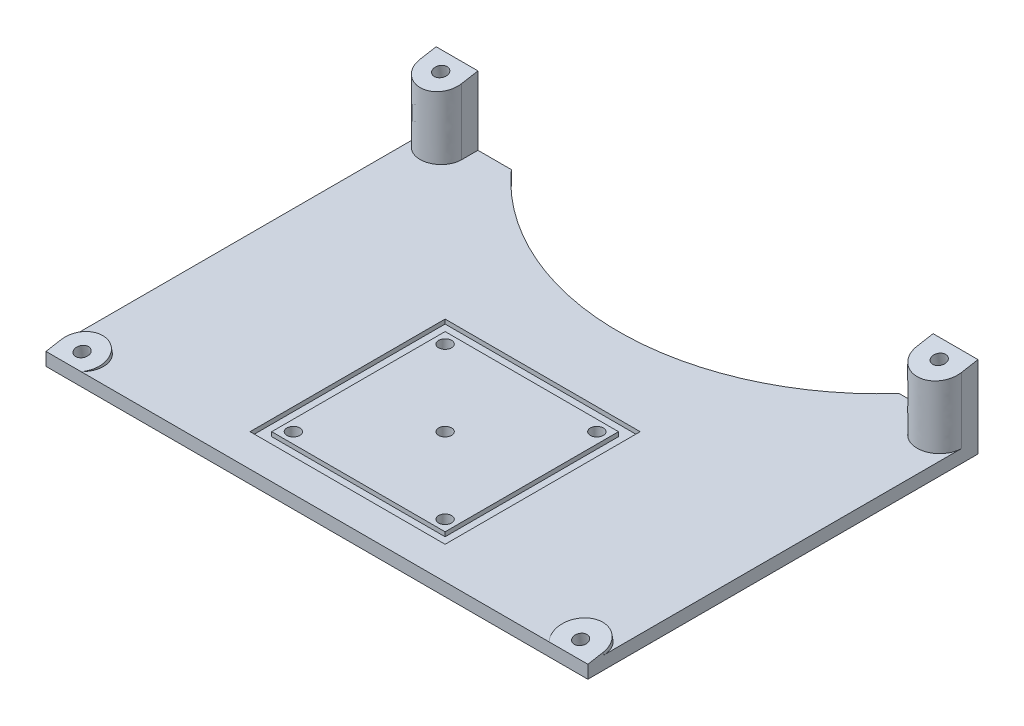
SolidWorks part; units mm, degrees
ref_plane "前视基准面" through (0, 0, 0) normal (0, 0, 1) x (1, 0, 0)
ref_plane "上视基准面" through (0, 0, 0) normal (0, 1, 0) x (1, 0, 0)
ref_plane "右视基准面" through (0, 0, 0) normal (1, 0, 0) x (0, 0, -1)
other "Configuration Table"
sketch "草图1" plane through (0, 0, 0) normal (0, 1, 0) x (1, 0, 0)
  line L1 (-62.5, 45) -> (62.5, 45)
  line L2 (-62.5, 45) -> (-62.5, -45)
  line L3 (-62.5, -45) -> (62.5, -45)
  line L4 (62.5, 45) -> (62.5, -45)
  line L5 (-62.5, 45) -> (62.5, -45) construction
  line L6 (-62.5, -45) -> (62.5, 45) construction
  point P0 (0, 0)
  dimension "D1" = 125
  dimension "D2" = 90
extrude "凸台-拉伸1" add sketch "草图1" along normal blind 3
sketch "草图3" plane through (62.5, 0, 0) normal (1, 0, 0) x (0, 0, -1)
  line L0 (-45, 3) -> (45, 18.8694)
  line L2 (45, 18.8694) -> (45, 3)
  line L3 (-45, 3) -> (45, 3) construction
  line L4 (-45, 3) -> (45, 3)
  dimension "D1" = 10
extrude "凸台-拉伸2" add sketch "草图3" against normal up to surface (125 mm away) up to face at (-62.5, 1.5, 0)
sketch "草图4" plane through (0, 10.605, 1.8699) normal (0, 0.9848, 0.1736) x (1, 0, 0)
  line L3 (-57.6776, 43.7689) -> (57.3224, 43.7689) construction
  line L4 (-57.6776, 43.7689) -> (-57.6776, -40.2311) construction
  line L5 (-57.6776, -40.2311) -> (57.3224, -40.2311) construction
  line L6 (57.3224, 43.7689) -> (57.3224, -40.2311) construction
  line L7 (-57.6776, 43.7689) -> (57.3224, -40.2311) construction
  line L8 (-57.6776, -40.2311) -> (57.3224, 43.7689) construction
  circle A0 centre (-57.6776, 43.7689) radius 1.5
  circle A1 centre (-57.6776, -40.2311) radius 1.5
  circle A2 centre (57.3224, -40.2311) radius 1.5
  circle A3 centre (57.3224, 43.7689) radius 1.5
  point P8 (-0.1776, 1.7689)
  dimension "D3" = 3
  dimension "D4" = 3
  dimension "D5" = 3
  dimension "D6" = 3
  dimension "D1" = 84
  dimension "D2" = 115
extrude "切除-拉伸1" cut sketch "草图4" against normal through all
sketch "草图6" plane through (0, 10.605, 1.8699) normal (0, 0.9848, 0.1736) x (1, 0, 0)
  line L0 (-62.5, 1.8988) -> (62.5, 1.8988) construction
  line L1 (-62.5, -43.7954) -> (-62.5, 47.593) construction
  line L2 (62.5, 47.593) -> (62.5, -43.7954) construction
  line L3 (0, 47.593) -> (0, -43.7954) construction
  line L4 (-62.5, 47.593) -> (62.5, 47.593) construction
  line L5 (-62.5, -43.7954) -> (62.5, -43.7954) construction
  line L6 (-62.5, 43.7689) -> (-62.5, -40.2311)
  line L7 (-54.7396, 47.593) -> (53.8318, 47.593)
  line L8 (62.5, 43.7689) -> (62.5, -40.2311)
  line L9 (-54.4294, -43.7954) -> (53.5669, -43.7954)
  arc A0 (-62.5, 43.7689) -> (-54.7396, 47.593) centre (-57.6776, 43.7689) ccw
  arc A1 (-54.4294, -43.7954) -> (-62.5, -40.2311) centre (-57.6776, -40.2311) ccw
  arc A2 (53.8318, 47.593) -> (62.5, 43.7689) centre (57.3224, 43.7689) ccw
  arc A3 (62.5, -40.2311) -> (53.5669, -43.7954) centre (57.3224, -40.2311) ccw
extrude "切除-拉伸2" cut sketch "草图6" against normal offset from surface (15.44 mm away) 3
sketch "草图7" plane through (0, 3, 0) normal (0, 1, 0) x (1, 0, 0)
  line L0 (-0.4313, -45) -> (-0.4313, -15) construction
  line L1 (-54.4294, -45) -> (53.5669, -45) construction
  line L3 (-17.9313, 2.5) -> (17.0687, 2.5) construction
  line L4 (-17.9313, 2.5) -> (-17.9313, -32.5) construction
  line L5 (-17.9313, -32.5) -> (17.0687, -32.5) construction
  line L6 (17.0687, 2.5) -> (17.0687, -32.5) construction
  line L7 (-17.9313, 2.5) -> (17.0687, -32.5) construction
  line L8 (-17.9313, -32.5) -> (17.0687, 2.5) construction
  circle A0 centre (-17.9313, 2.5) radius 1.5
  circle A1 centre (-17.9313, -32.5) radius 1.5
  circle A2 centre (17.0687, 2.5) radius 1.5
  circle A3 centre (17.0687, -32.5) radius 1.5
  circle A4 centre (-0.4313, -15) radius 1.5
  dimension "D4" = 3
  dimension "D5" = 3
  dimension "D6" = 3
  dimension "D7" = 3
  dimension "D8" = 3
  dimension "D1" = 30
  dimension "D2" = 35
  dimension "D3" = 35
extrude "切除-拉伸3" cut sketch "草图7" against normal through all
sketch "草图8" plane through (0, 3, 0) normal (0, 1, 0) x (1, 0, 0)
  line L0 (-17.9313, -32.5) -> (17.0687, 2.5) construction
  line L1 (-20.4313, 5) -> (19.5687, 5)
  line L2 (-20.4313, 5) -> (-20.4313, -35)
  line L3 (-20.4313, -35) -> (19.5687, -35)
  line L4 (19.5687, 5) -> (19.5687, -35)
  line L5 (-20.4313, 5) -> (19.5687, -35) construction
  line L6 (-20.4313, -35) -> (19.5687, 5) construction
  line L7 (-17.9313, 2.5) -> (17.0687, -32.5) construction
  line L9 (-22.9313, 7.5) -> (22.0687, 7.5)
  line L10 (-22.9313, 7.5) -> (-22.9313, -37.5)
  line L11 (-22.9313, -37.5) -> (22.0687, -37.5)
  line L12 (22.0687, 7.5) -> (22.0687, -37.5)
  line L13 (-22.9313, 7.5) -> (22.0687, -37.5) construction
  line L14 (-22.9313, -37.5) -> (22.0687, 7.5) construction
  point P0 (-0.4313, -15)
  point P9 (-0.4313, -15)
  dimension "D1" = 40
  dimension "D2" = 45
extrude "切除-拉伸4" cut sketch "草图8" against normal blind 1
sketch "草图10" plane through (0, 3, 0) normal (0, 1, 0) x (1, 0, 0)
  line L0 (-52.8553, 41.234) -> (-52.8553, 45)
  line L1 (52.2562, 45) -> (-52.9751, 45) construction
  line L2 (-54.7396, 45) -> (-62.5, 45)
  line L3 (-62.5, 45) -> (-62.5, 41.234)
  line L5 (-62.5, 45) -> (-62.5, 41.234)
  line L6 (-62.5, 45) -> (-52.8553, 45)
  line L7 (52.1447, 41.234) -> (52.1447, 45)
  line L8 (52.1447, 45) -> (62.5, 45)
  line L9 (62.5, 41.234) -> (62.5, 45)
  line L10 (62.5, 45) -> (53.8318, 45)
  line L11 (62.5, 41.234) -> (62.5, 45)
  ellipse E1 centre (-57.6776, 41.234) end of major axis (-52.8553, 41.234) minor radius 4.7491 (-62.5, 41.234) -> (-54.7396, 45) ccw
  ellipse E2 centre (-57.6776, 41.234) end of major axis (-52.8553, 41.234) minor radius 4.7491 (-62.5, 41.234) -> (-52.8553, 41.234) ccw
  ellipse E3 centre (57.3224, 41.234) end of major axis (62.5, 41.234) minor radius 5.099 (53.8318, 45) -> (62.5, 41.234) ccw
  ellipse E4 centre (57.3224, 41.234) end of major axis (62.5, 41.234) minor radius 5.099 (52.1447, 41.234) -> (62.5, 41.234) ccw
  dimension "D1" = 0
  dimension "D2" = 0
extrude "凸台-拉伸5" add sketch "草图10" along normal up to surface (15.8694 mm away)
sketch "草图13" plane through (0, 10.605, 1.8699) normal (0, 0.9848, 0.1736) x (1, 0, 0)
  circle A0 centre (-57.6776, 43.7689) radius 1.5
  circle A1 centre (57.3224, 43.7689) radius 1.5
extrude "切除-拉伸6" cut sketch "草图13" against normal blind 12
sketch "草图14" plane through (0, 3, 0) normal (0, 1, 0) x (1, 0, 0)
  circle A0 centre (-0.4313, 85) radius 60 construction
  circle A1 centre (-0.4313, 85) radius 60
extrude "切除-拉伸11" cut sketch "草图14" against normal blind 10
